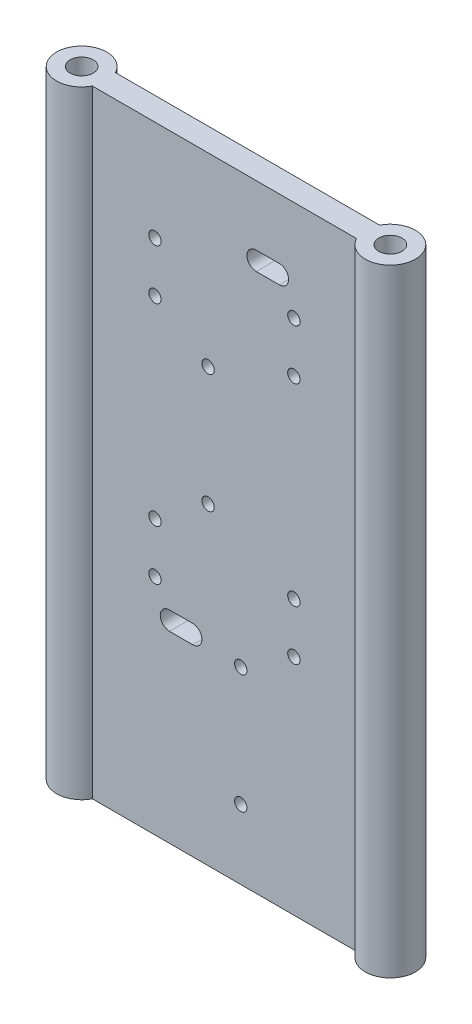
SolidWorks part; units mm, degrees
ref_plane "Front Plane" through (0, 0, 0) normal (0, 0, 1) x (1, 0, 0)
ref_plane "Top Plane" through (0, 0, 0) normal (0, 1, 0) x (1, 0, 0)
ref_plane "Right Plane" through (0, 0, 0) normal (1, 0, 0) x (0, 0, -1)
sketch "Sketch1" plane through (0, 0, 0) normal (0, 1, 0) x (1, 0, 0)
  line L0 (-43.4768, 3.81) -> (43.4768, 3.81)
  line L1 (-43.4768, -3.81) -> (43.4768, -3.81)
  arc A0 (-43.4768, 3.81) -> (-43.4768, -3.81) centre (-50.8, 0) ccw
  arc A1 (43.4768, 3.81) -> (43.4768, -3.81) centre (50.8, 0) cw
  dimension "D1" = 8.255
  dimension "D2" = 8.255
  dimension "D3" = 7.62
  dimension "D4" = 3.81
  dimension "D5" = 101.6
  dimension "D6" = 50.8
extrude "Boss-Extrude1" add sketch "Sketch1" along normal blind 203.2
sketch "Sketch2" plane through (0, 0, 0) normal (0, -1, 0) x (1, 0, 0)
  circle A0 centre (-50.8, 0) radius 3.81
  circle A1 centre (50.8, 0) radius 3.81
  dimension "D1" = 7.62
  dimension "D2" = 7.62
  dimension "D3" = 101.6
  dimension "D4" = 50.8
extrude "Cut-Extrude1" cut sketch "Sketch2" against normal blind 203.2
sketch "Sketch3" plane through (0, 0, 3.81) normal (0, 0, 1) x (1, 0, 0)
  line L0 (-43.4768, 203.2) -> (43.4768, 203.2) construction
  line L1 (-43.4768, 0) -> (43.4768, 0) construction
  line L2 (43.4768, 203.2) -> (43.4768, 0) construction
  line L3 (18.0768, 180.34) -> (10.4568, 180.34) construction
  line L5 (-43.4768, 203.2) -> (-43.4768, 0) construction
  line L7 (18.0768, 177.292) -> (10.4568, 177.292)
  line L8 (18.0768, 183.388) -> (10.4568, 183.388)
  line L9 (-18.0768, 63.5) -> (-10.4568, 63.5) construction
  line L10 (-18.0768, 66.548) -> (-10.4568, 66.548)
  line L11 (-18.0768, 60.452) -> (-10.4568, 60.452)
  arc A12 (18.0768, 177.292) -> (18.0768, 183.388) centre (18.0768, 180.34) ccw
  arc A13 (10.4568, 183.388) -> (10.4568, 177.292) centre (10.4568, 180.34) ccw
  arc A14 (-18.0768, 66.548) -> (-18.0768, 60.452) centre (-18.0768, 63.5) ccw
  arc A15 (-10.4568, 60.452) -> (-10.4568, 66.548) centre (-10.4568, 63.5) ccw
  point P0 (14.2668, 180.34)
  point P3 (-14.2668, 63.5)
  dimension "D2" = 3.048
  dimension "D3" = 7.62
  dimension "D5" = 7.62
  dimension "D11" = 3.048
  dimension "D7" = 25.4
  dimension "D8" = 25.4
  dimension "D9" = 22.86
  dimension "D10" = 63.5
extrude "Cut-Extrude2" cut sketch "Sketch3" against normal blind 36.322 and the other way blind 28.956
sketch "Sketch5" plane through (0, 0, -3.81) normal (0, 0, -1) x (-1, 0, 0)
  line L0 (-43.4768, 0) -> (43.4768, 0) construction
  line L2 (-43.4768, 203.2) -> (43.4768, 203.2) construction
  circle A0 centre (-22.86, 170.18) radius 2.032
  circle A1 centre (-22.86, 153.67) radius 2.032
  circle A2 centre (22.86, 170.18) radius 2.032
  circle A3 centre (22.86, 153.67) radius 2.032
  circle A4 centre (-22.86, 90.17) radius 2.032
  circle A5 centre (-22.86, 73.66) radius 2.032
  circle A6 centre (22.86, 90.17) radius 2.032
  circle A7 centre (22.86, 73.66) radius 2.032
  dimension "D1" = 4.064
  dimension "D2" = 4.064
  dimension "D3" = 4.064
  dimension "D4" = 4.064
  dimension "D9" = 4.064
  dimension "D10" = 4.064
  dimension "D11" = 4.064
  dimension "D12" = 4.064
  dimension "D5" = 45.72
  dimension "D6" = 16.51
  dimension "D7" = 22.86
  dimension "D8" = 33.02
  dimension "D13" = 45.72
  dimension "D14" = 22.86
  dimension "D15" = 16.51
  dimension "D16" = 73.66
extrude "Cut-Extrude3" cut sketch "Sketch5" against normal blind 45.974
sketch "Sketch6" plane through (0, 0, 3.81) normal (0, 0, 1) x (1, 0, 0)
  line L0 (43.4768, 203.2) -> (43.4768, 0) construction
  line L1 (-43.4768, 203.2) -> (-43.4768, 0) construction
  line L2 (-43.4768, 203.2) -> (43.4768, 203.2) construction
  line L3 (-43.4768, 0) -> (43.4768, 0) construction
  circle A0 centre (5.3768, 61.976) radius 2.032
  circle A1 centre (5.3768, 22.86) radius 2.032
  circle A2 centre (-5.3768, 142.24) radius 2.032
  circle A3 centre (-5.3768, 103.124) radius 2.032
  dimension "D1" = 4.064
  dimension "D2" = 4.064
  dimension "D3" = 4.064
  dimension "D4" = 4.064
  dimension "D5" = 39.116
  dimension "D6" = 39.116
  dimension "D7" = 38.1
  dimension "D8" = 38.1
  dimension "D9" = 60.96
  dimension "D10" = 22.86
extrude "Cut-Extrude4" cut sketch "Sketch6" against normal blind 7.62
